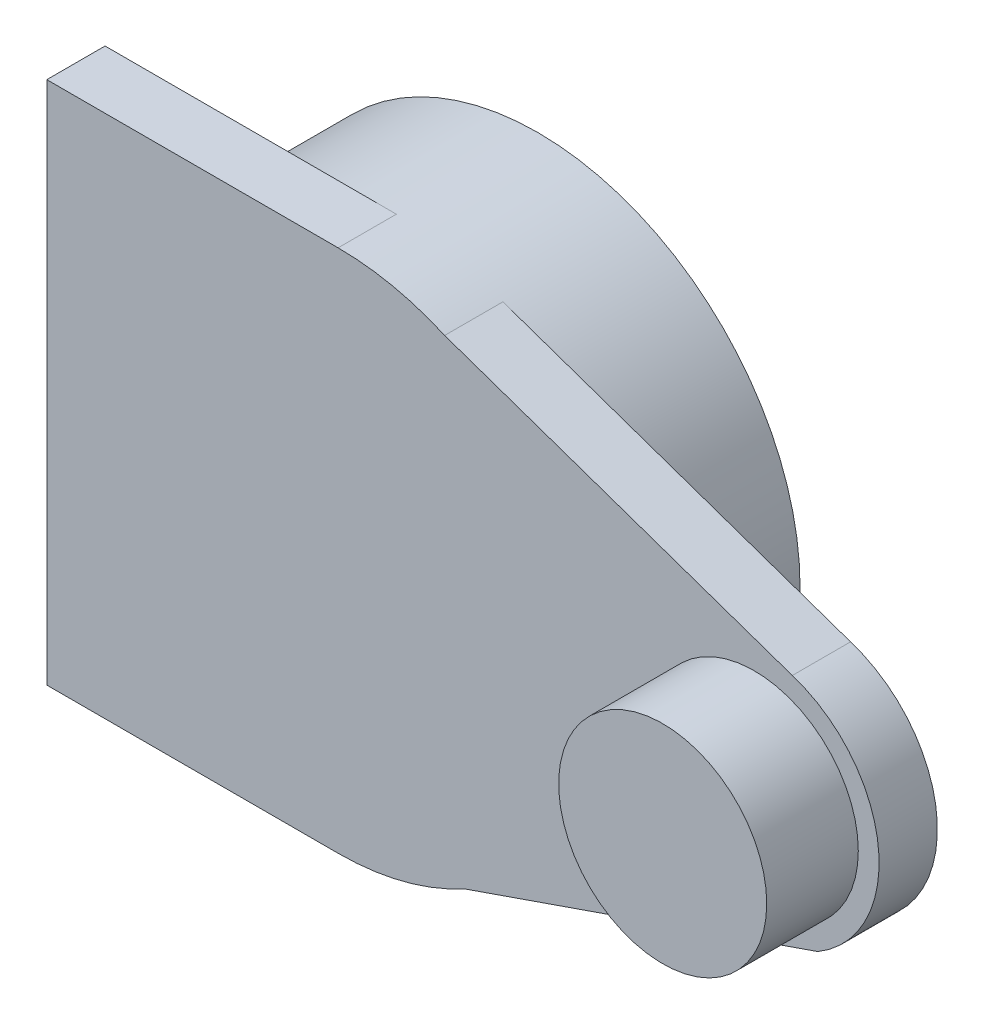
SolidWorks part; units mm, degrees
ref_plane "Front Plane" through (0, 0, 0) normal (0, 0, 1) x (1, 0, 0)
ref_plane "Top Plane" through (0, 0, 0) normal (0, 1, 0) x (1, 0, 0)
ref_plane "Right Plane" through (0, 0, 0) normal (1, 0, 0) x (0, 0, -1)
sketch "Sketch1" plane through (0, 0, 0) normal (0, 0, 1) x (1, 0, 0)
  circle A0 centre (0, 0) radius 31.5
  dimension "D1" = 63
extrude "Boss-Extrude1" add sketch "Sketch1" along normal blind 17
sketch "Sketch2" plane through (0, 0, 17) normal (0, 0, 1) x (1, 0, 0)
  line L0 (35, 21.0781) -> (35, 26.5798)
  line L1 (-35, 31.5) -> (0, 31.5)
  line L2 (-35, -31.5) -> (-35, 31.5)
  line L3 (-35, -31.5) -> (0, -31.5)
  line L5 (-35, -31.5) -> (26.6426, 23.9783) construction
  line L6 (-35, 31.5) -> (35, -31.5) construction
  arc A0 (57.6439, -12.9062) -> (54.5696, 14.287) centre (50, 0) ccw
  circle A1 centre (0, 0) radius 31.5 construction
  arc A2 (12.8014, 28.7815) -> (0, 31.5) centre (0, 0) ccw
  arc A3 (0, -31.5) -> (15.1228, -27.6324) centre (0, 0) ccw
  spline S0 degree 1 poles (12.8014, 28.7815) (54.5696, 14.287) knots 0 0 1 1
  spline S1 degree 1 poles (15.1228, -27.6324) (57.6439, -12.9062) knots 0 0 1 1
  point P0 (0, 0)
  point P6 (50, 0)
  point P7 (68.3657, -57.4187)
  circle M4 centre (0, 0) radius 31.5
  dimension "D4" = 30
  dimension "D2" = 63
  dimension "D3" = 50
extrude "Boss-Extrude2" add sketch "Sketch2" along normal blind 7 contours L2 L3 L1 M4 | M4 | S1 A0 S0 M4
sketch "Sketch3" plane through (0, 0, 24) normal (0, 0, 1) x (1, 0, 0)
  circle A0 centre (50, 0) radius 12.5
  dimension "D1" = 25
extrude "Boss-Extrude3" add sketch "Sketch3" along normal blind 11 contours A0
